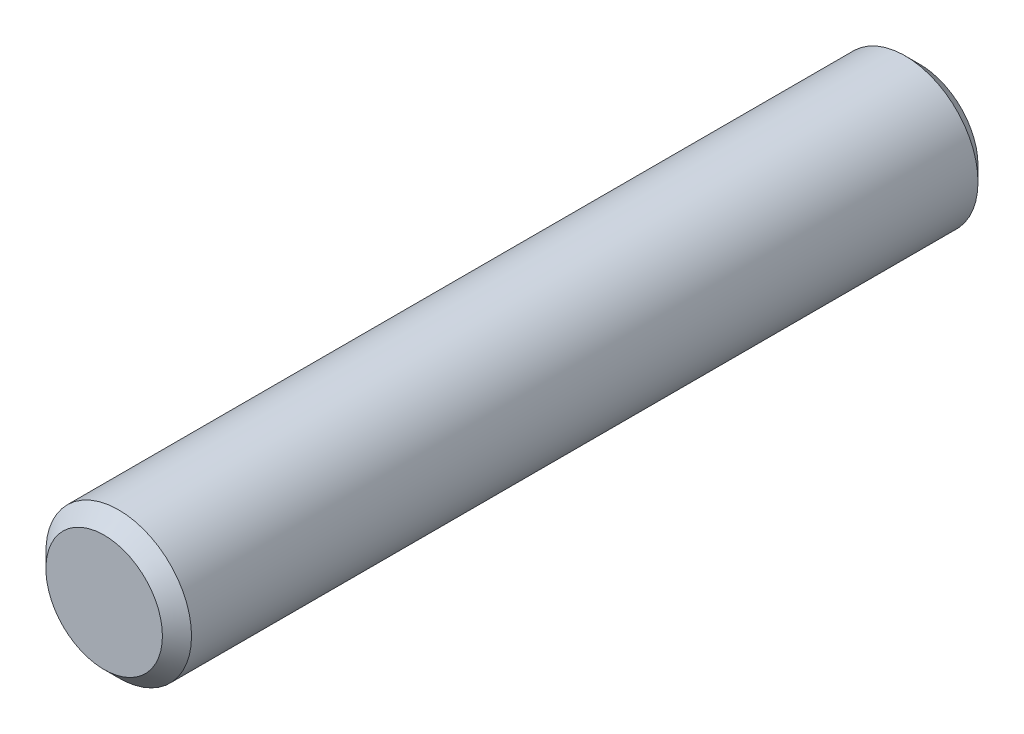
SolidWorks part; units mm, degrees
ref_plane "Front Plane" through (0, 0, 0) normal (0, 0, 1) x (1, 0, 0)
ref_plane "Top Plane" through (0, 0, 0) normal (0, 1, 0) x (1, 0, 0)
ref_plane "Right Plane" through (0, 0, 0) normal (1, 0, 0) x (0, 0, -1)
sketch "Sketch1" plane through (0, 0, 0) normal (0, 0, 1) x (1, 0, 0)
  circle A0 centre (0, 0) radius 2.5
  dimension "D1" = 5
extrude "Boss-Extrude1" add sketch "Sketch1" along normal blind 28
chamfer "Chamfer1" distance 0.5 angle 45 2 edges at (2.5, 0, 0) (2.5, 0, 28)
